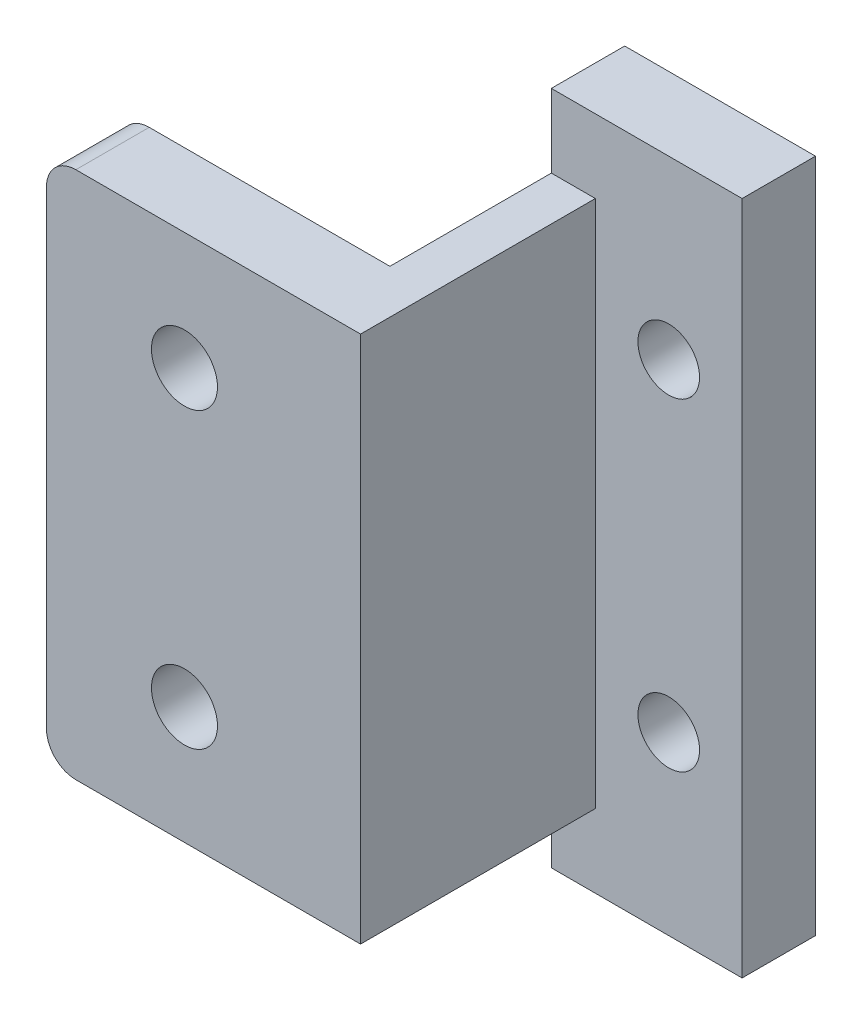
SolidWorks part; units mm, degrees
ref_plane "Plan de face" through (0, 0, 0) normal (0, 0, 1) x (1, 0, 0)
ref_plane "Plan de dessus" through (0, 0, 0) normal (0, 1, 0) x (1, 0, 0)
ref_plane "Plan de droite" through (0, 0, 0) normal (1, 0, 0) x (0, 0, -1)
sketch "Esquisse1" plane through (0, 0, 0) normal (0, 0, 1) x (1, 0, 0)
  line L0 (-7.4, 36) -> (-7.4, 0)
  line L4 (10, 3) -> (10, 33)
  line L5 (7, 36) -> (-14.4, 36)
  line L6 (-14.4, 36) -> (-14.4, 0)
  line L7 (-14.4, 0) -> (7, 0)
  line L8 (10, 3) -> (10, 33)
  line L9 (7, 36) -> (-7.4, 36)
  line L11 (-7.4, 0) -> (7, 0)
  line L12 (-14.4, 36) -> (-14.4, 0) construction
  circle A0 centre (2, 8) radius 2.25 construction
  circle A1 centre (2, 28) radius 2.25 construction
  arc A2 (10, 33) -> (7, 36) centre (7, 33) ccw
  arc A3 (7, 0) -> (10, 3) centre (7, 3) ccw
  arc A4 (10, 33) -> (7, 36) centre (7, 33) ccw
  arc A5 (7, 0) -> (10, 3) centre (7, 3) ccw
  circle A6 centre (2, 8) radius 2.25
  circle A7 centre (2, 28) radius 2.25
  dimension "D2" = 7
  dimension "D1" = 0
extrude "Boss.-Extru.1" add sketch "Esquisse1" along normal blind 5
sketch "Esquisse2" plane through (0, 0, 5) normal (0, 0, 1) x (1, 0, 0)
  line L0 (10, 3) -> (10, 33) construction
  line L1 (10, 3) -> (10, 33)
  line L2 (7, 36) -> (11, 36)
  line L3 (11, 114.3721) -> (11, -324.4) construction
  line L4 (11, 36) -> (11, 41)
  line L5 (11, 41) -> (24, 41)
  line L6 (24, 41) -> (24, -5)
  line L7 (24, -5) -> (11, -5)
  line L8 (11, -5) -> (11, 0)
  line L9 (11, 0) -> (7, 0)
  arc A0 (7, 0) -> (10, 3) centre (7, 3) ccw construction
  arc A1 (10, 33) -> (7, 36) centre (7, 33) ccw construction
  arc A2 (7, 0) -> (10, 3) centre (7, 3) ccw
  arc A3 (10, 33) -> (7, 36) centre (7, 33) ccw
  point P12 (11, 38.5)
  dimension "D1" = 5
  dimension "D2" = 5
  dimension "D3" = 13
extrude "Boss.-Extru.2" add sketch "Esquisse2" against normal up to surface (21 mm away)
sketch "Esquisse4" plane through (0, 0, 5) normal (0, 0, 1) x (1, 0, 0)
  line L1 (24, 41) -> (11, 41)
  line L2 (24, 41) -> (24, -5)
  line L3 (24, -5) -> (11, -5)
  line L4 (11, 41) -> (11, -5)
extrude "Enlèv. mat.-Extru.2" cut sketch "Esquisse4" against normal blind 16
sketch "Esquisse9" plane through (11, 0, 0) normal (1, 0, 0) x (0, 0, -1)
  line L4 (-5, 36) -> (-5, 0)
  line L5 (-5, 0) -> (11, 0)
  line L6 (11, 0) -> (11, 36)
  line L7 (11, 36) -> (-5, 36)
  line L8 (-5, 36) -> (-5, 0)
  line L9 (-5, 0) -> (11, 0)
  line L10 (11, 0) -> (11, 36)
  line L11 (11, 36) -> (-5, 36)
  dimension "D1" = 0
extrude "Boss.-Extru.3" add sketch "Esquisse9" along normal blind 3
sketch "Esquisse10" plane through (0, 36, 0) normal (0, 1, 0) x (1, 0, 0)
  line L1 (11, 16) -> (7, 16)
  line L2 (11, 16) -> (11, 0)
  line L3 (11, 0) -> (7, 0)
  line L4 (7, 16) -> (7, 0)
extrude "Enlèv. mat.-Extru.6" cut sketch "Esquisse10" against normal blind 43
fillet "Congé1" radius 2 2 edges at (-7.4, 0, 2.5) (-7.4, 36, 2.5)
sketch "Esquisse11" plane through (0, 0, -11) normal (0, 0, 1) x (1, 0, 0)
  line L0 (14, 36) -> (24, 36) construction
  line L1 (24, -5) -> (24, 41) construction
  line L2 (19, 36) -> (19, -5) construction
  line L3 (11, -5) -> (24, -5) construction
  line L4 (24, 41) -> (11, 41) construction
  circle A0 centre (19, 29) radius 2.1
  circle A1 centre (19, 7) radius 2.1
  dimension "D1" = 4.2
  dimension "D2" = 4.2
  dimension "D3" = 12
  dimension "D4" = 12
extrude "Enlèv. mat.-Extru.7" cut sketch "Esquisse11" against normal blind 43
